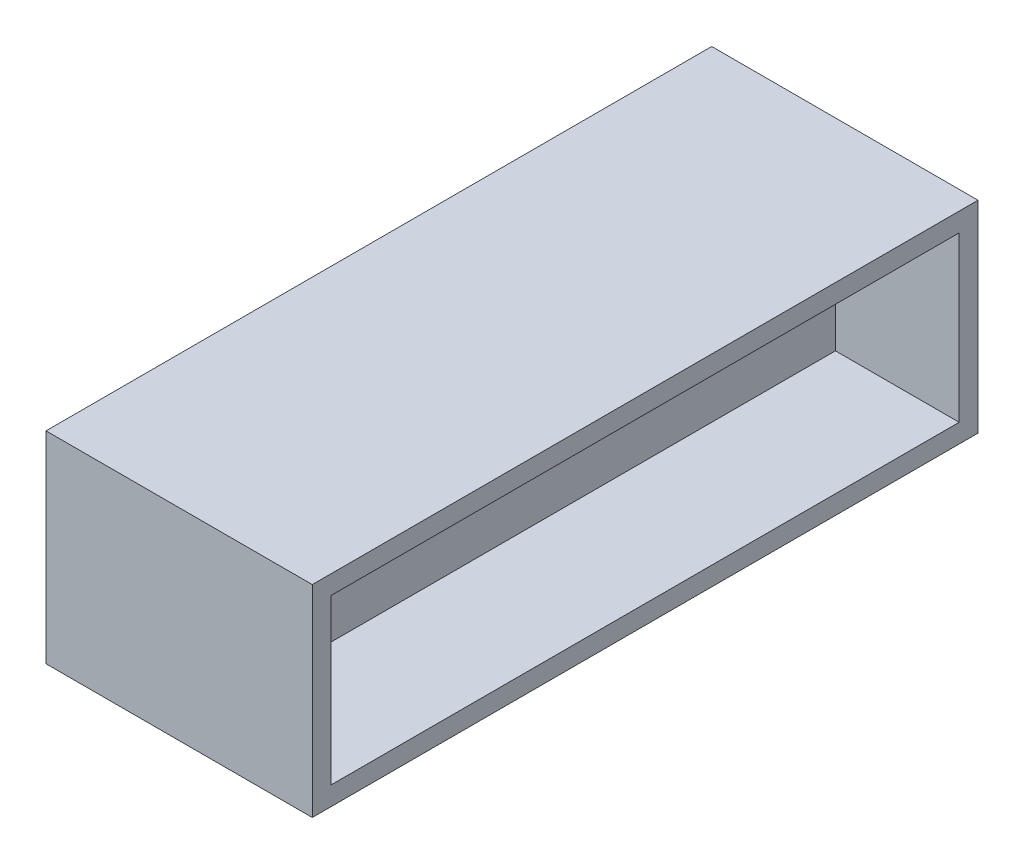
SolidWorks part; units mm, degrees
ref_plane "Front Plane" through (0, 0, 0) normal (0, 0, 1) x (1, 0, 0)
ref_plane "Top Plane" through (0, 0, 0) normal (0, 1, 0) x (1, 0, 0)
ref_plane "Right Plane" through (0, 0, 0) normal (1, 0, 0) x (0, 0, -1)
sketch "Sketch1" plane through (0, 0, 0) normal (0, 0, 1) x (1, 0, 0)
  line L1 (-21.2, -16.06) -> (21.2, -16.06)
  line L2 (-21.2, -16.06) -> (-21.2, 16.06)
  line L3 (-21.2, 16.06) -> (21.2, 16.06)
  line L4 (21.2, -16.06) -> (21.2, 16.06)
  line L5 (-21.2, -16.06) -> (21.2, 16.06) construction
  line L6 (-21.2, 16.06) -> (21.2, -16.06) construction
  point P0 (0, 0)
  dimension "D1" = 32.12
  dimension "D2" = 42.4
extrude "Boss-Extrude1" add sketch "Sketch1" along normal blind 3
sketch "Sketch2" plane through (0, 0, 3) normal (0, 0, 1) x (1, 0, 0)
  line L0 (21.2, -16.06) -> (21.2, 16.06) construction
  line L1 (-21.2, 16.06) -> (21.2, 16.06)
  line L2 (-21.2, 16.06) -> (-21.2, 13.06)
  line L3 (-21.2, 13.06) -> (21.2, 13.06)
  line L4 (21.2, 16.06) -> (21.2, 13.06)
  line L6 (-21.2, -16.06) -> (21.2, -16.06)
  line L7 (-21.2, -16.06) -> (-21.2, -13.06)
  line L8 (-21.2, -13.06) -> (21.2, -13.06)
  line L9 (21.2, -16.06) -> (21.2, -13.06)
  line L10 (-1.5, -16.06) -> (1.5, -16.06)
  line L11 (-1.5, -16.06) -> (-1.5, 16.06)
  line L12 (-1.5, 16.06) -> (1.5, 16.06)
  line L13 (1.5, -16.06) -> (1.5, 16.06)
  line L14 (-1.5, -16.06) -> (1.5, 16.06) construction
  line L15 (-1.5, 16.06) -> (1.5, -16.06) construction
  point P11 (0, 0)
  line M4 (21.2, -16.06) -> (21.2, 16.06)
  line M5 (21.2, 16.06) -> (-21.2, 16.06)
  line M6 (-21.2, 16.06) -> (-21.2, -16.06)
  dimension "D1" = 3
  dimension "D2" = 3
  dimension "D3" = 3
extrude "Boss-Extrude2" add sketch "Sketch2" along normal blind 100 contours L8 L13 L3 L11 | L3 L11 L1 M6 | L13 L3 M4 M5 | L3 L13 L1 L11
sketch "Sketch3" plane through (0, 0, 103) normal (0, 0, 1) x (1, 0, 0)
  line L1 (-21.2, -16.06) -> (21.2, -16.06)
  line L2 (-21.2, -16.06) -> (-21.2, 16.06)
  line L3 (-21.2, 16.06) -> (21.2, 16.06)
  line L4 (21.2, -16.06) -> (21.2, 16.06)
extrude "Boss-Extrude3" add sketch "Sketch3" along normal blind 3
